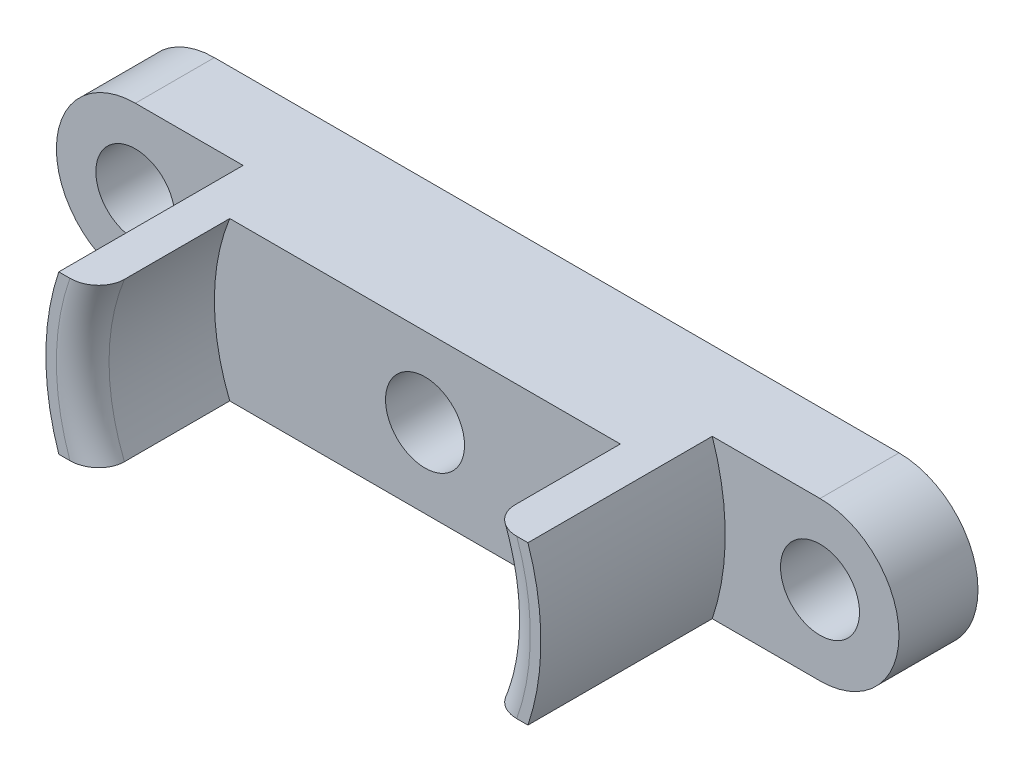
SolidWorks part; units mm, degrees
ref_plane "前视基准面" through (0, 0, 0) normal (0, 0, 1) x (1, 0, 0)
ref_plane "上视基准面" through (0, 0, 0) normal (0, 1, 0) x (1, 0, 0)
ref_plane "右视基准面" through (0, 0, 0) normal (1, 0, 0) x (0, 0, -1)
sketch "草图1" plane through (0, 0, 0) normal (0, 1, 0) x (1, 0, 0)
  line L0 (0, 0) -> (0, -16.0369) construction
  line L5 (0, 0) -> (0, 5)
  line L6 (0, 5) -> (20, 5)
  line L7 (20, 5) -> (20, 2)
  line L8 (20, 2) -> (9.4, 2)
  line L9 (9.4, 2) -> (9.4, 0)
  line L10 (9.4, 0) -> (0, 0)
  dimension "D1" = 9.4
  dimension "D2" = 20
  dimension "D3" = 3
  dimension "D4" = 2
revolve "旋转3" add sketch "草图1" angle 360 about L0
sketch "草图2" plane through (0, 0, 0) normal (0, 0, 1) x (1, 0, 0)
  line L0 (13, 0) -> (-13, 0) construction
  line L1 (-24.8312, -21.974) -> (24.8312, -21.974)
  line L2 (-24.8312, -21.974) -> (-24.8312, 21.974)
  line L3 (-24.8312, 21.974) -> (24.8312, 21.974)
  line L4 (24.8312, -21.974) -> (24.8312, 21.974)
  line L5 (-24.8312, -21.974) -> (24.8312, 21.974) construction
  line L6 (-24.8312, 21.974) -> (24.8312, -21.974) construction
  line L11 (13, -3) -> (-13, -3)
  line L12 (13, 3) -> (-13, 3)
  arc A0 (13, -3) -> (13, 3) centre (13, 0) ccw
  arc A1 (-13, 3) -> (-13, -3) centre (-13, 0) ccw
  point P7 (0, 0)
  circle M3 centre (0, 0) radius 9.4
  dimension "D1" = 3
  dimension "D2" = 26
extrude "切除-拉伸1" cut sketch "草图2" against normal blind 10 contours L1 L4 L3 L2 A1 L12 A0 L11 M3 | L12 M3 | L11 M3
sketch "草图3" plane through (0, 0, 0) normal (0, 0, 1) x (1, 0, 0)
  circle A0 centre (0, 0) radius 1.5
  circle A1 centre (13, 0) radius 1.5
  circle A2 centre (-13, 0) radius 1.5
  dimension "D1" = 3
  dimension "D2" = 3
  dimension "D3" = 3
  dimension "D4" = 26
  dimension "D5" = 13
extrude "切除-拉伸2" cut sketch "草图3" against normal through all
sketch "草图5" plane through (0, 0, 0) normal (0, 0, 1) x (1, 0, 0)
  line L0 (-8.9084, 3) -> (8.9084, 3) construction
  line L1 (-8.9084, -3) -> (8.9084, -3) construction
  line L2 (-8.9084, 3) -> (8.9084, 3)
  line L3 (-8.9084, -3) -> (8.9084, -3)
  arc A0 (8.9084, -3) -> (8.9084, 3) centre (0, 0) ccw construction
  arc A1 (-8.9084, 3) -> (-8.9084, -3) centre (0, 0) ccw construction
  arc A2 (8.9084, -3) -> (8.9084, 3) centre (0, 0) ccw
  arc A3 (-8.9084, 3) -> (-8.9084, -3) centre (0, 0) ccw
  circle A4 centre (0, 0) radius 8
  arc M2 (-8.9084, 3) -> (-8.9084, -3) centre (0, 0) ccw
  line M3 (-8.9084, -3) -> (8.9084, -3)
  arc M4 (8.9084, -3) -> (8.9084, 3) centre (0, 0) ccw
  line M5 (8.9084, 3) -> (-8.9084, 3)
  dimension "D1" = 16
extrude "凸台-拉伸2" add sketch "草图5" along normal blind 5 contours A4 M5 M2 M3 | A4 M3 M4 M5
fillet "圆角2" radius 1 2 edges at (-8, 0, 5) (8, 0, 5)
sketch "草图4" plane through (0, 0, -5) normal (0, 0, -1) x (-1, 0, 0)
  line L0 (-4, 6.2258) -> (-4, -6.2258)
  line L1 (4, 6.2258) -> (4, -6.2258)
  circle A0 centre (0, 0) radius 7.4
  line M8 (13, 3) -> (-13, 3)
  line M10 (-13, -3) -> (13, -3)
  dimension "D1" = 14.8
  dimension "D2" = 8
extrude "凸台-拉伸1" [suppressed] add sketch "草图4" against normal blind 10 contours L0 A0 M8 | A0 L1 M8 | L1 A0 M10 | A0 L0 M10
fillet "圆角1" [suppressed] radius 2
